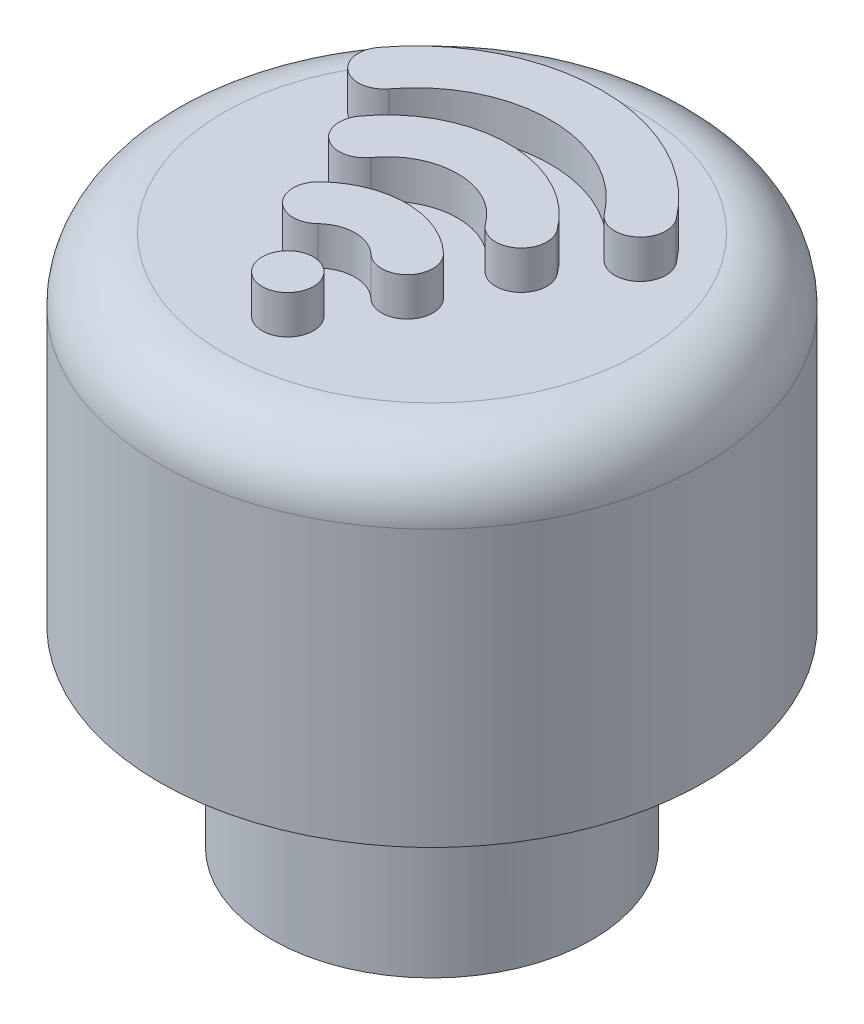
SolidWorks part; units mm, degrees
ref_plane "Front Plane" through (0, 0, 0) normal (0, 0, 1) x (1, 0, 0)
ref_plane "Top Plane" through (0, 0, 0) normal (0, 1, 0) x (1, 0, 0)
ref_plane "Right Plane" through (0, 0, 0) normal (1, 0, 0) x (0, 0, -1)
sketch "Sketch1" plane through (0, 0, 0) normal (0, 1, 0) x (1, 0, 0)
  circle A0 centre (0, 0) radius 4.25
  dimension "D1" = 8.5
extrude "Boss-Extrude1" add sketch "Sketch1" along normal blind 5.3 contours A0
sketch "Sketch2" plane through (0, 0, 0) normal (0, -1, 0) x (1, 0, 0)
  circle A0 centre (0, 0) radius 2.5
  dimension "D1" = 5
extrude "Boss-Extrude2" add sketch "Sketch2" along normal blind 3
shell "Shell2" thickness 0.7
fillet "Fillet1" radius 1 1 edges at (0, 5.3, 4.25)
sketch "Sketch5" plane through (0, 5.3, 0) normal (0, 1, 0) x (1, 0, 0)
  point P0 (0, 0)
sketch "Sketch3" plane through (0, 5.3, 0) normal (0, 1, 0) x (1, 0, 0)
  line L1 (-3.2465, 0) -> (3.2465, 0) construction
  line L2 (0, 1.25) -> (0, 3.25) construction
  line L3 (0, 3.25) -> (0, -3.25) construction
  circle A0 centre (0, 0) radius 3.25 construction
  arc A1 (-0.6902, -1.0764) -> (0.6902, -1.0764) centre (0, -1.8) cw construction
  arc A2 (0.9663, -0.787) -> (-0.9663, -0.787) centre (0, -1.8) ccw
  arc A3 (0.4141, -1.3659) -> (-0.4141, -1.3659) centre (0, -1.8) ccw
  arc A4 (0.4141, -1.3659) -> (0.9663, -0.787) centre (0.6902, -1.0764) ccw
  arc A5 (-0.9663, -0.787) -> (-0.4141, -1.3659) centre (-0.6902, -1.0764) ccw
  arc A6 (-1.2198, 0.173) -> (1.2198, 0.173) centre (0, -0.7) cw construction
  arc A7 (1.5451, 0.4058) -> (-1.5451, 0.4058) centre (0, -0.7) ccw
  arc A8 (0.8945, -0.0598) -> (-0.8945, -0.0598) centre (0, -0.7) ccw
  arc A9 (0.8945, -0.0598) -> (1.5451, 0.4058) centre (1.2198, 0.173) ccw
  arc A10 (-1.5451, 0.4058) -> (-0.8945, -0.0598) centre (-1.2198, 0.173) ccw
  arc A11 (-2, 1.25) -> (2, 1.25) centre (0, -0.25) cw construction
  arc A12 (2.32, 1.49) -> (-2.32, 1.49) centre (0, -0.25) ccw
  arc A13 (1.68, 1.01) -> (-1.68, 1.01) centre (0, -0.25) ccw
  arc A14 (1.68, 1.01) -> (2.32, 1.49) centre (2, 1.25) ccw
  arc A15 (-2.32, 1.49) -> (-1.68, 1.01) centre (-2, 1.25) ccw
  circle A16 centre (0, -2.25) radius 0.4
  point P5 (2.32, 1.49)
  point P12 (0, -0.8)
  point P20 (0, 0.8)
  point P25 (0.6875, 0.1503)
  point P29 (0, 2.25)
  point P35 (0, 1.85)
  point P36 (0, 0.4)
  point P37 (0, -1.2)
  point P38 (0, 0.1503)
  point P40 (-2.32, 1.49)
  point P41 (1.5451, 0.4058)
  point P42 (-1.5451, 0.4058)
  point P43 (-0.9663, -0.787)
  point P44 (0.9663, -0.787)
  point P45 (-1.5451, 0.4058)
  point P46 (1.4526, -0.1523)
  point P47 (-1.4526, -0.1523)
  point P48 (0.9797, -1.3525)
  point P49 (-0.9797, -1.3525)
  dimension "D1" = 1
  dimension "D2" = 1.5
  dimension "D3" = 2.5
  dimension "D6" = 0.8
  dimension "D8" = 0.8
  dimension "D9" = 0.8
  dimension "D10" = 0.8
  dimension "D4" = 4
  dimension "D5" = 1.6
  dimension "D7" = 1
  dimension "D11" = 1
  dimension "D12" = 0.8
extrude "Boss-Extrude4" add sketch "Sketch3" along normal blind 0.6
